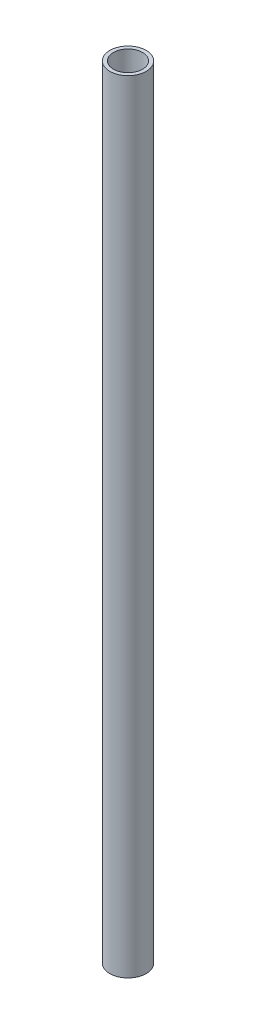
SolidWorks part; units mm, degrees
material "Laiton de décolletage, UNS C36000"
ref_plane "Plan de face" through (0, 0, 0) normal (0, 0, 1) x (1, 0, 0)
ref_plane "Plan de dessus" through (0, 0, 0) normal (0, 1, 0) x (1, 0, 0)
ref_plane "Plan de droite" through (0, 0, 0) normal (1, 0, 0) x (0, 0, -1)
sketch "Esquisse1" plane through (0, 0, 0) normal (0, 0, 1) x (1, 0, 0)
  line L0 (0, 107.5) -> (0, -107.5)
  point P4 (0, 0)
  dimension "D1" = 215
other "Tube rond 10X1(1)"
ref_plane "Plan1" through (0, 107.5, 0) normal (0, -1, 0) x (1, 0, 0)
sketch "tube rond" plane through (0, 107.5, 0) normal (0, -1, 0) x (1, 0, 0)
  line L0 (-5, 0) -> (5, 0) construction
  circle A0 centre (0, 0) radius 5
  circle A1 centre (0, 0) radius 4
  point P6 (0, 0)
  dimension "d" = 10
  dimension "e" = 1
